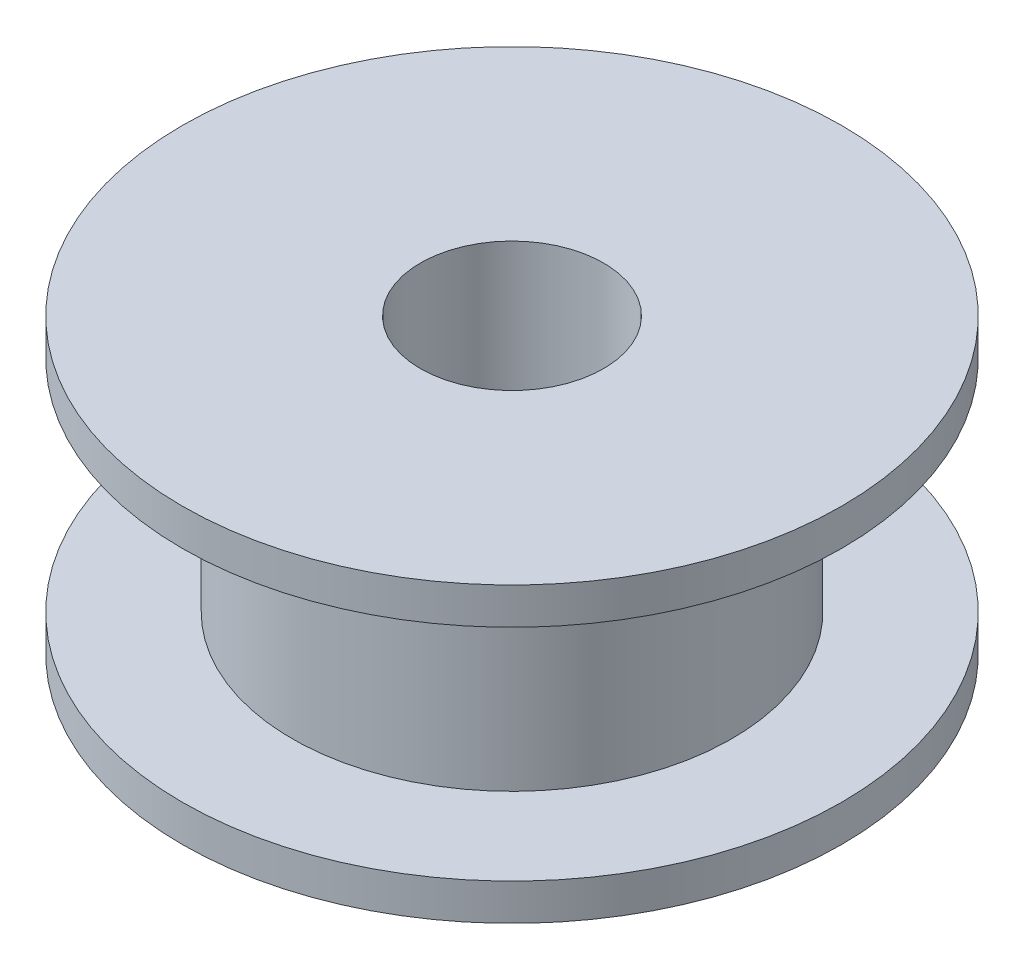
SolidWorks part; units mm, degrees
ref_plane "Front Plane" through (0, 0, 0) normal (0, 0, 1) x (1, 0, 0)
ref_plane "Top Plane" through (0, 0, 0) normal (0, 1, 0) x (1, 0, 0)
ref_plane "Right Plane" through (0, 0, 0) normal (1, 0, 0) x (0, 0, -1)
sketch "Sketch1" plane through (0, 0, 0) normal (0, 1, 0) x (1, 0, 0)
  circle A0 centre (0, 0) radius 9
extrude "Boss-Extrude1" add sketch "Sketch1" along normal blind 8
sketch "Sketch2" plane through (0, 0, 0) normal (1, 0, 0) x (0, 0, -1)
  line L0 (-9, 8) -> (-9, 0) construction
  line L1 (-9, 7) -> (-6, 7)
  line L2 (-9, 7) -> (-9, 1)
  line L3 (-9, 1) -> (-6, 1)
  line L4 (-6, 7) -> (-6, 1)
  line L5 (9, 8) -> (-9, 8) construction
  dimension "D1" = 3
  dimension "D2" = 6
  dimension "D3" = 1
sketch "Sketch3" plane through (0, 8, 0) normal (0, 1, 0) x (1, 0, 0)
  circle A0 centre (0, 0) radius 2.5
extrude "Cut-Extrude1" cut sketch "Sketch3" against normal through all
ref_axis "Axis1" through (0, 0, 0) along (0, 1, 0)
revolve "Cut-Revolve1" cut sketch "Sketch2" angle 360 about axis through (0, 0, 0) along (0, 1, 0)
